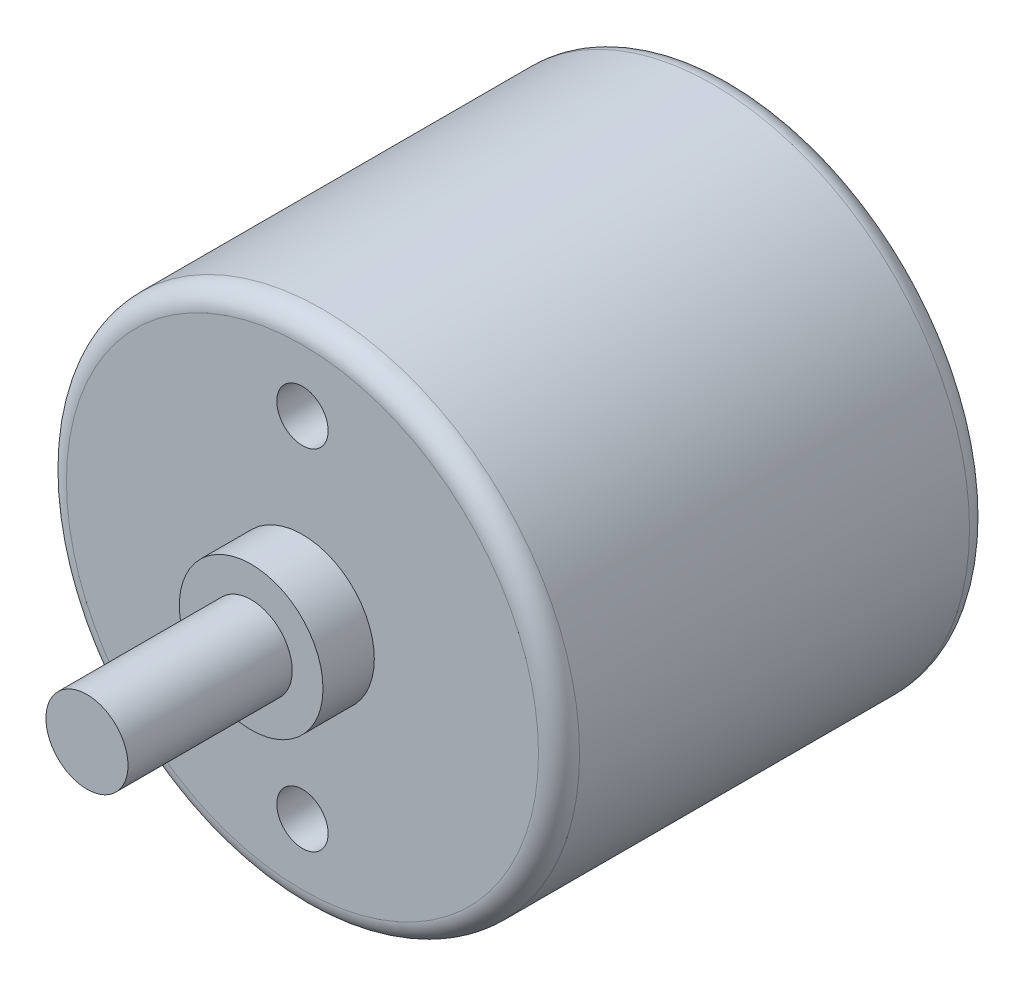
SolidWorks part; units mm, degrees
material "201.0-T43 Molde de fundição com isolamento (SS)"
ref_plane "Plano frontal" through (0, 0, 0) normal (0, 0, 1) x (1, 0, 0)
ref_plane "Plano superior" through (0, 0, 0) normal (0, 1, 0) x (1, 0, 0)
ref_plane "Plano direito" through (0, 0, 0) normal (1, 0, 0) x (0, 0, -1)
sketch "Esboço1" plane through (0, 0, 0) normal (0, 0, 1) x (1, 0, 0)
  circle A0 centre (0, 0) radius 12.5
  dimension "D1" = 25
extrude "Ressalto-extrusão1" add sketch "Esboço1" along normal blind 21
sketch "Esboço2" plane through (0, 0, 21) normal (0, 0, 1) x (1, 0, 0)
  circle A0 centre (0, 0) radius 3.5
  dimension "D1" = 7
extrude "Ressalto-extrusão2" add sketch "Esboço2" along normal blind 2.5
sketch "Esboço3" plane through (0, 0, 23.5) normal (0, 0, 1) x (1, 0, 0)
  circle A0 centre (0, 0) radius 2
  dimension "D1" = 4
fillet "Filete1" radius 1 2 edges at (12.5, 0, 21) (12.5, 0, 0)
extrude "Ressalto-extrusão3" add sketch "Esboço3" along normal blind 8
sketch "Esboço4" plane through (0, 0, 21) normal (0, 0, 1) x (1, 0, 0)
  circle A0 centre (0, 8.5) radius 1.25
  circle A1 centre (0, -8.5) radius 1.25
  point P8 (0, 0)
  dimension "D1" = 2.5
  dimension "D2" = 2
  dimension "D3" = 17
extrude "Corte-extrusão1" cut sketch "Esboço4" against normal blind 10
